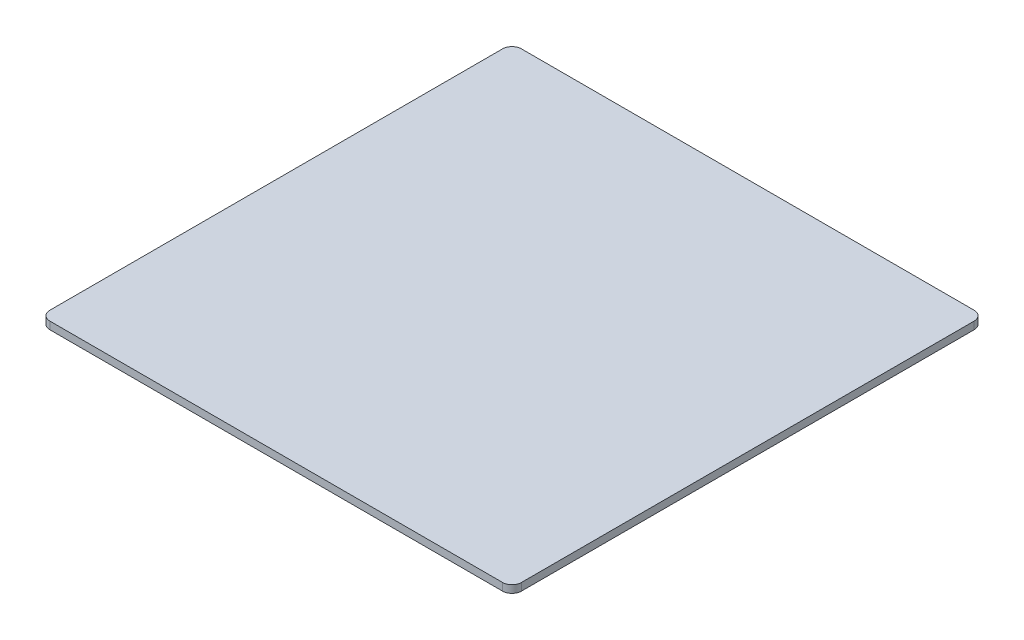
SolidWorks part; units mm, degrees
ref_plane "前视基准面" through (0, 0, 0) normal (0, 0, 1) x (1, 0, 0)
ref_plane "上视基准面" through (0, 0, 0) normal (0, 1, 0) x (1, 0, 0)
ref_plane "右视基准面" through (0, 0, 0) normal (1, 0, 0) x (0, 0, -1)
sketch "草图1" plane through (0, 0, 0) normal (0, 1, 0) x (1, 0, 0)
  line L1 (-50, -50) -> (50, -50)
  line L2 (-50, -50) -> (-50, 50)
  line L3 (-50, 50) -> (50, 50)
  line L4 (50, -50) -> (50, 50)
  line L5 (-50, -50) -> (50, 50) construction
  line L6 (-50, 50) -> (50, -50) construction
  point P0 (0, 0)
  dimension "D1" = 100
  dimension "D2" = 100
extrude "凸台-拉伸1" add sketch "草图1" along normal blind 1.6
fillet "圆角1" radius 2 4 edges at (50, 0.8, -50) (-50, 0.8, -50) (-50, 0.8, 50) (50, 0.8, 50)
